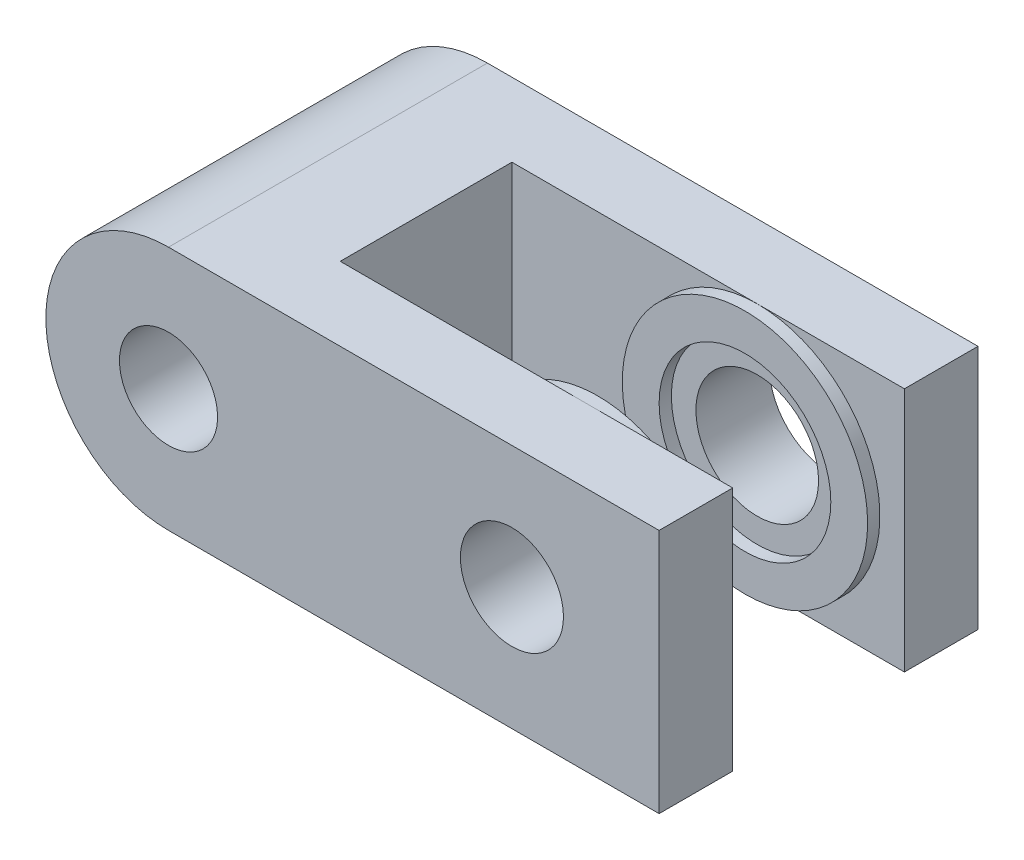
SolidWorks part; units mm, degrees
ref_plane "Ebene vorne" through (0, 0, 0) normal (0, 0, 1) x (1, 0, 0)
ref_plane "Ebene oben" through (0, 0, 0) normal (0, 1, 0) x (1, 0, 0)
ref_plane "Ebene rechts" through (0, 0, 0) normal (1, 0, 0) x (0, 0, -1)
sketch "Skizze1" plane through (0, 0, 0) normal (0, 0, 1) x (1, 0, 0)
  line L1 (0, 5) -> (20, 5)
  line L2 (0, 5) -> (0, -5)
  line L3 (0, -5) -> (20, -5)
  line L4 (20, 5) -> (20, -5)
  line L5 (0, 5) -> (20, -5) construction
  line L6 (0, -5) -> (20, 5) construction
  circle A0 centre (0, 0) radius 5
  circle A1 centre (0, 0) radius 2
  point P7 (10, 0)
  dimension "D1" = 10
  dimension "D3" = 4
  dimension "D2" = 20
extrude "Aufsatz-Linear austragen1" add sketch "Skizze1" along normal blind 13 contours A1 L2 A0 | A0 L3 L4 L1 | A1 L2 A0
sketch "Skizze2" plane through (0, 5, 0) normal (0, 1, 0) x (1, 0, 0)
  line L0 (20, -13) -> (20, 0) construction
  line L1 (20, -3) -> (4, -3)
  line L2 (20, -3) -> (20, -10)
  line L3 (20, -10) -> (4, -10)
  line L4 (4, -3) -> (4, -10)
  line L5 (20, -3) -> (4, -10) construction
  line L6 (20, -10) -> (4, -3) construction
  line L7 (0, 0) -> (20, 0) construction
  line L8 (0, -13) -> (20, -13) construction
  point P4 (12, -6.5)
  dimension "D1" = 3
  dimension "D2" = 3
  dimension "D3" = 7
  dimension "D4" = 16
extrude "Schnitt-Linear austragen1" cut sketch "Skizze2" against normal blind 10
sketch "Skizze4" plane through (0, 0, 3) normal (0, 0, 1) x (1, 0, 0)
  line L0 (20, 0) -> (14, 0) construction
  line L1 (20, 5) -> (20, -5) construction
  circle A0 centre (14, 0) radius 2.5
  dimension "D1" = 5
  dimension "D2" = 6
extrude "Schnitt-Linear austragen2" cut sketch "Skizze4" against normal up to surface (3 mm away) up to face at (8.75, 0, 0)
sketch "Skizze5" plane through (0, 0, 0) normal (0, 0, -1) x (-1, 0, 0)
  circle A0 centre (0, 0) radius 3.5
  circle A1 centre (0, 0) radius 2
  dimension "D1" = 7
extrude "Schnitt-Linear austragen3" cut sketch "Skizze5" against normal blind 4
sketch "Skizze6" plane through (0, 0, 10) normal (0, 0, -1) x (-1, 0, 0)
  circle A0 centre (-14, 0) radius 2.1
extrude "Schnitt-Linear austragen4" cut sketch "Skizze6" against normal blind 4
sketch "Skizze7" plane through (0, 0, 3) normal (0, 0, 1) x (1, 0, 0)
  circle A0 centre (14, 0) radius 3.5
  circle A1 centre (14, 0) radius 5
  circle A2 centre (14, 0) radius 2.5 construction
  dimension "D1" = 7
extrude "Aufsatz-Linear austragen2" add sketch "Skizze7" along normal blind 0.5
sketch "Skizze8" plane through (0, 0, 10) normal (0, 0, -1) x (-1, 0, 0)
  circle A0 centre (-14, 0) radius 2.1
  circle A1 centre (-14, 0) radius 5
  circle A2 centre (-14, 0) radius 2.1 construction
extrude "Aufsatz-Linear austragen3" add sketch "Skizze8" along normal blind 0.5
